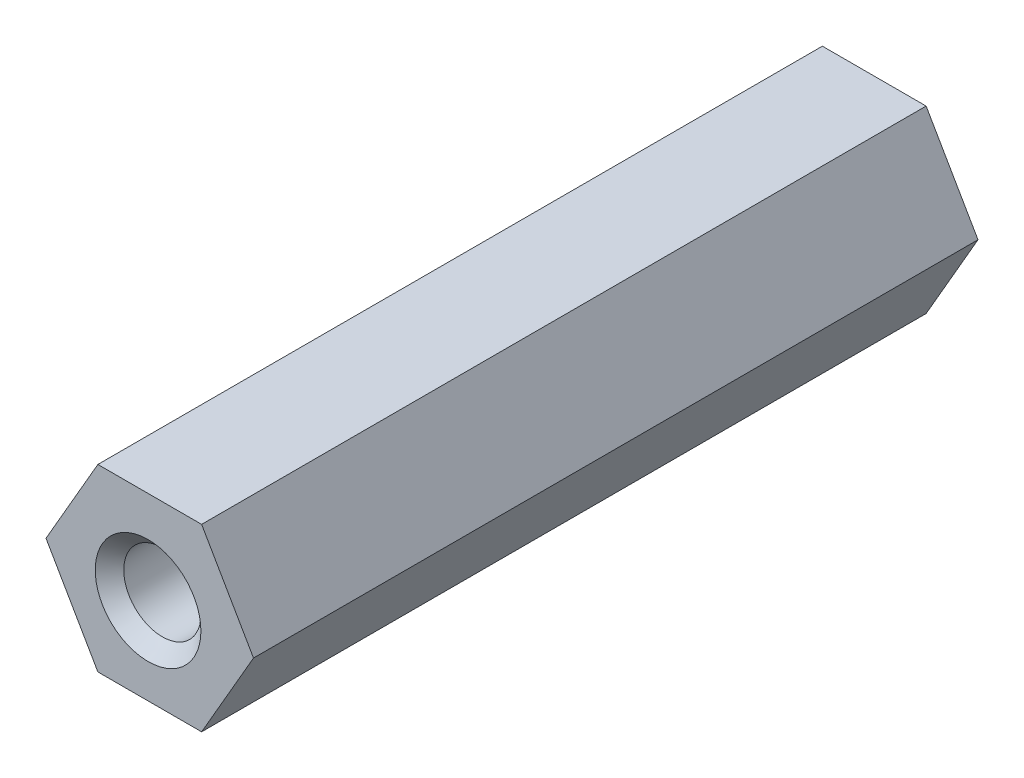
SolidWorks part; units mm, degrees
other "Defeature"
material "6061 Alloy"
ref_plane "Front Plane" through (0, 0, 0) normal (0, 0, 1) x (1, 0, 0)
ref_plane "Top Plane" through (0, 0, 0) normal (0, 1, 0) x (1, 0, 0)
ref_plane "Right Plane" through (0, 0, 0) normal (1, 0, 0) x (0, 0, -1)
sketch "Sketch1" plane through (0, 0, 0) normal (0, 0, 1) x (1, 0, 0)
  line L1 (3.6373, 0) -> (1.8187, 3.15)
  line L2 (1.8187, 3.15) -> (-1.8187, 3.15)
  line L3 (-1.8187, 3.15) -> (-3.6373, 0)
  line L4 (-3.6373, 0) -> (-1.8187, -3.15)
  line L5 (-1.8187, -3.15) -> (1.8187, -3.15)
  line L6 (1.8187, -3.15) -> (3.6373, 0)
  circle A0 centre (0, 0) radius 3.15 construction
  dimension "D1" = 6.3
extrude "Boss-Extrude1" add sketch "Sketch1" against normal mid plane 25.4
hole_wizard "#6-32 Tapped Hole8" positions "3DSketch13" profile "Sketch27" tap size "#6-32" standard "Ansi Inch" end condition through all
sketch3d "3DSketch13"
  point P0 (-0.0588, -0.1018, 12.7)
  dimension "D1" = 3.58
  dimension "D2" = 3.58
sketch "Sketch27" plane through (-0.0588, -0.1018, 12.7) normal (1, 0, 0) x (0, -1, 0)
  line L0 (0, 0) -> (0, 25.4)
  line L1 (0, 25.4) -> (1.3525, 25.4)
  line L2 (1.3525, 25.4) -> (1.3525, 0)
  line L5 (1.3525, 0) -> (0, 0)
  line L11 (0, -6.35) -> (0, 107.95) construction
  dimension "Thru Tap Drill Dia." = 2.7051
  dimension "Thru Tap Drill Depth" = 25.4
cosmetic thread "Hole Thread12" parameters "D2"=3.5052
chamfer "Chamfer1" distance 0.5 angle 45 1 edges at (1.2938, -0.1018, 12.7)
chamfer "Chamfer2" distance 0.5 angle 45 1 edges at (1.2938, -0.1018, -12.7)
